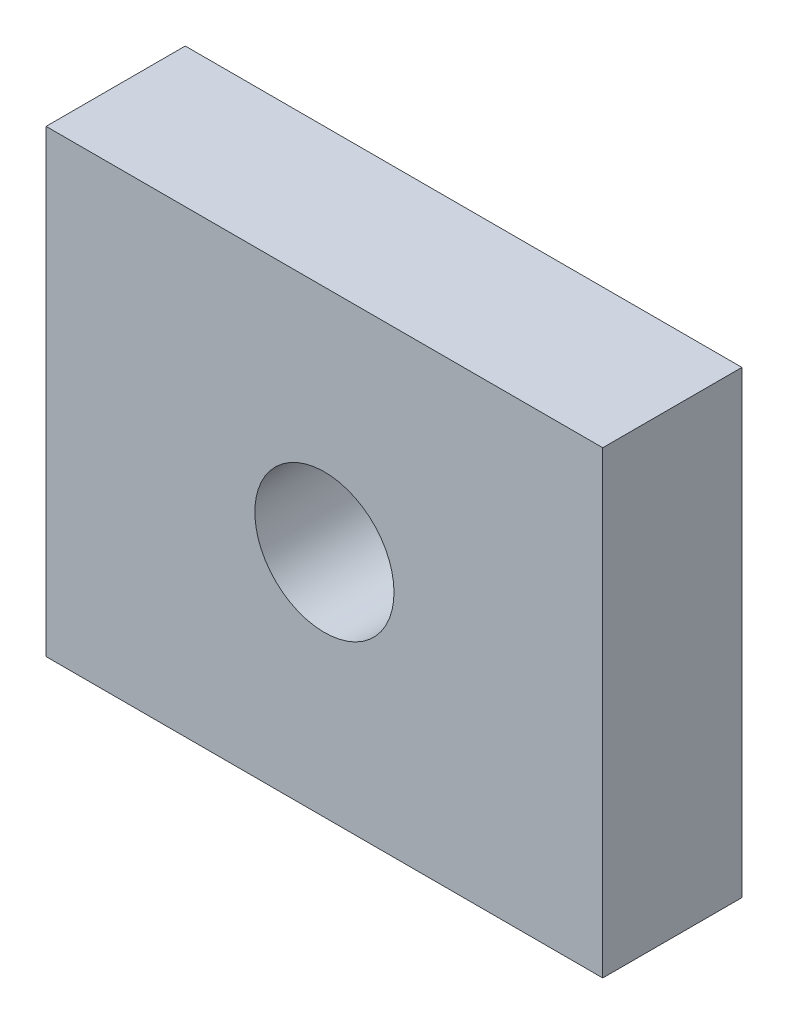
SolidWorks part; units mm, degrees
ref_plane "Plan de face" through (0, 0, 0) normal (0, 0, 1) x (1, 0, 0)
ref_plane "Plan de dessus" through (0, 0, 0) normal (0, 1, 0) x (1, 0, 0)
ref_plane "Plan de droite" through (0, 0, 0) normal (1, 0, 0) x (0, 0, -1)
sketch "Esquisse1" plane through (0, 0, 0) normal (0, 0, 1) x (1, 0, 0)
  line L0 (0, 8.25) -> (20, 8.25) construction
  line L1 (0, 0) -> (20, 0)
  line L2 (0, 0) -> (0, 16.5)
  line L3 (0, 16.5) -> (20, 16.5)
  line L4 (20, 0) -> (20, 16.5)
  circle A0 centre (10, 8.25) radius 2.5
  dimension "D2" = 16.5
  dimension "D3" = 20
extrude "Boss.-Extru.1" add sketch "Esquisse1" along normal blind 5
